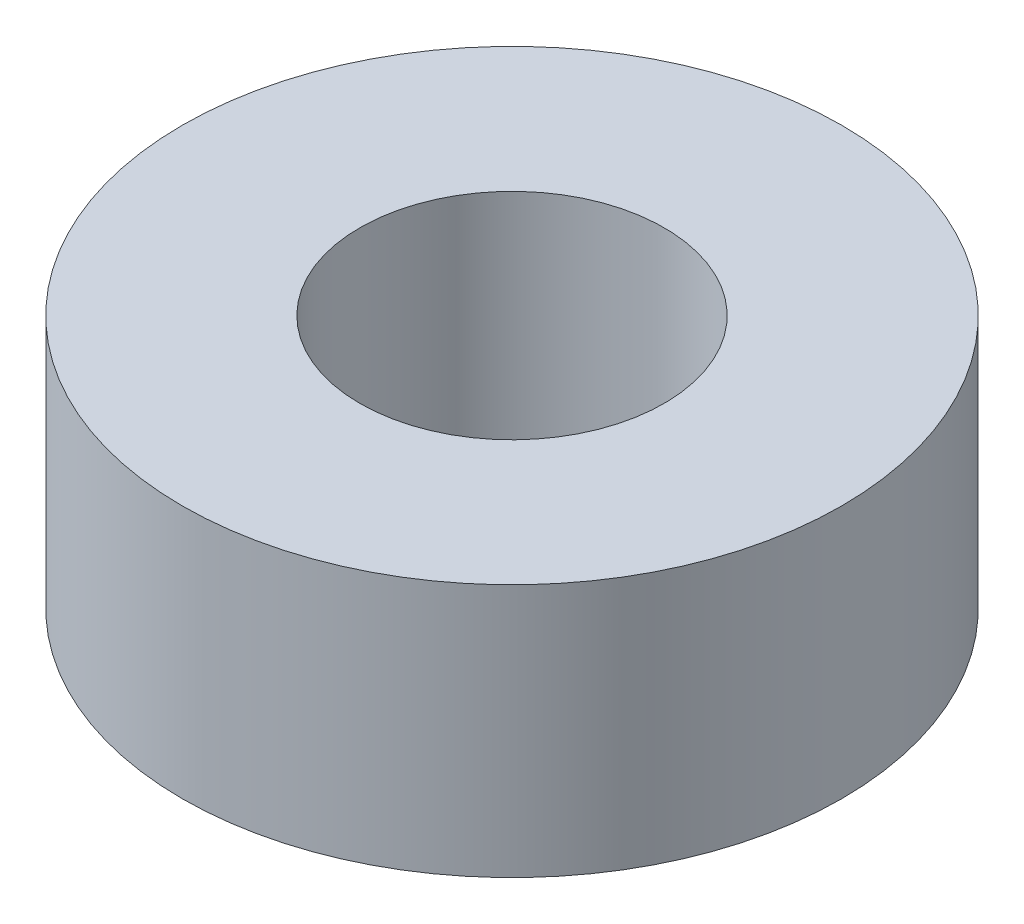
SolidWorks part; units mm, degrees
ref_plane "Plan de face" through (0, 0, 0) normal (0, 0, 1) x (1, 0, 0)
ref_plane "Plan de dessus" through (0, 0, 0) normal (0, 1, 0) x (1, 0, 0)
ref_plane "Plan de droite" through (0, 0, 0) normal (1, 0, 0) x (0, 0, -1)
sketch "Esquisse1" plane through (0, 0, 0) normal (0, 1, 0) x (1, 0, 0)
  circle A0 centre (0, 0) radius 6.5
  circle A1 centre (0, 0) radius 3
  dimension "D1" = 13
  dimension "D2" = 6
extrude "Boss.-Extru.1" add sketch "Esquisse1" along normal blind 5
